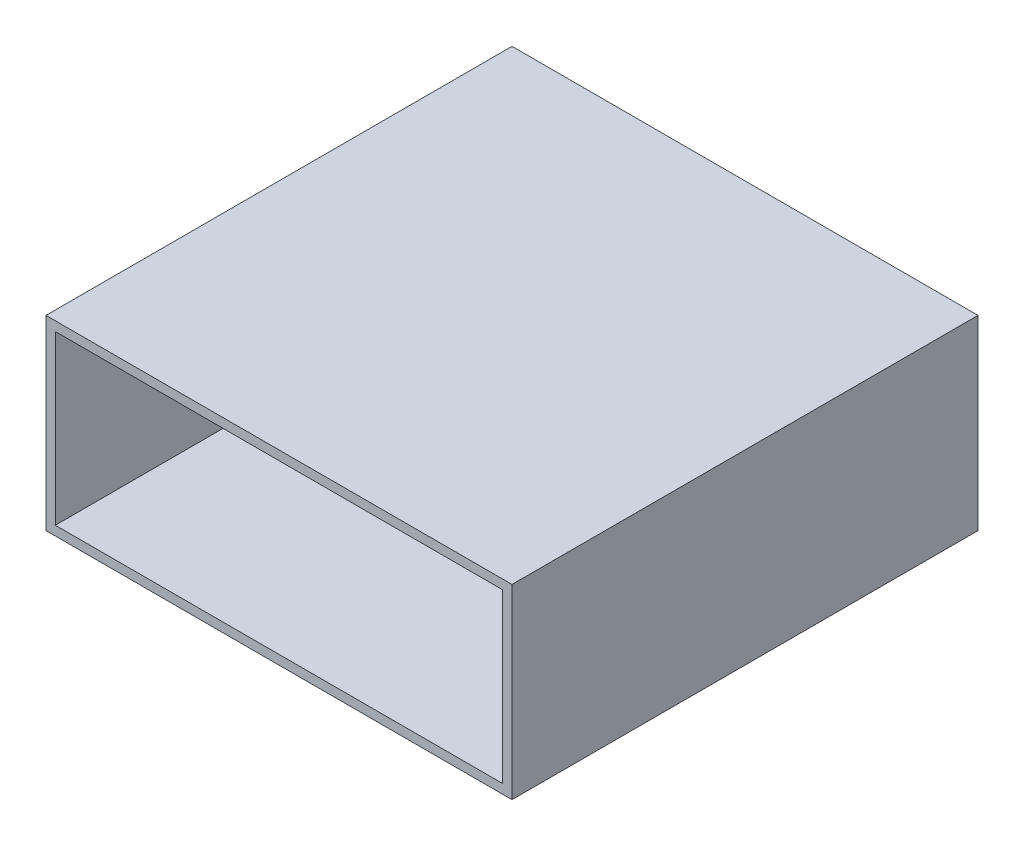
SolidWorks part; units mm, degrees
ref_plane "前视基准面" through (0, 0, 0) normal (0, 0, 1) x (1, 0, 0)
ref_plane "上视基准面" through (0, 0, 0) normal (0, 1, 0) x (1, 0, 0)
ref_plane "右视基准面" through (0, 0, 0) normal (1, 0, 0) x (0, 0, -1)
other "Configuration Table"
sketch "草图1" plane through (0, 0, 0) normal (0, 0, 1) x (1, 0, 0)
  line L1 (0, 0) -> (50, 0)
  line L2 (0, 0) -> (0, 20)
  line L3 (0, 20) -> (50, 20)
  line L4 (50, 0) -> (50, 20)
  line L5 (1, 1) -> (49, 1)
  line L6 (1, 1) -> (1, 19)
  line L7 (1, 19) -> (49, 19)
  line L8 (49, 1) -> (49, 19)
  dimension "D1" = 50
  dimension "D2" = 20
  dimension "D3" = 1
  dimension "D4" = 1
  dimension "D5" = 1
  dimension "D6" = 1
extrude "凸台-拉伸1" add sketch "草图1" along normal blind 50
